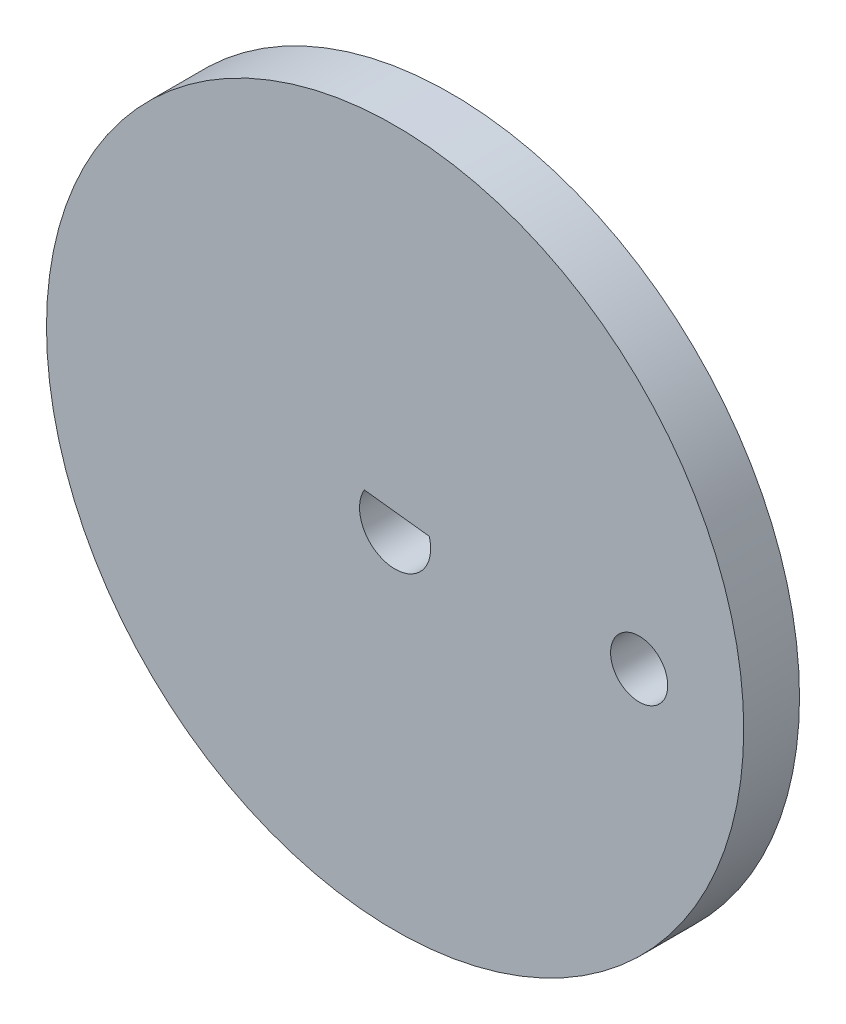
SolidWorks part; units mm, degrees
ref_plane "前视基准面" through (0, 0, 0) normal (0, 0, 1) x (1, 0, 0)
ref_plane "上视基准面" through (0, 0, 0) normal (0, 1, 0) x (1, 0, 0)
ref_plane "右视基准面" through (0, 0, 0) normal (1, 0, 0) x (0, 0, -1)
other "Configuration Table"
sketch "草图1" plane through (0, 0, 0) normal (0, 0, 1) x (1, 0, 0)
  line L0 (4.894, 1.4347) -> (-4.4239, 2.5376)
  circle A0 centre (0, 0) radius 50
  arc A1 (-4.4239, 2.5376) -> (4.894, 1.4347) centre (0, 0) ccw
  circle A2 centre (35, 0) radius 4.1
extrude "凸台-拉伸1" add sketch "草图1" along normal blind 8
